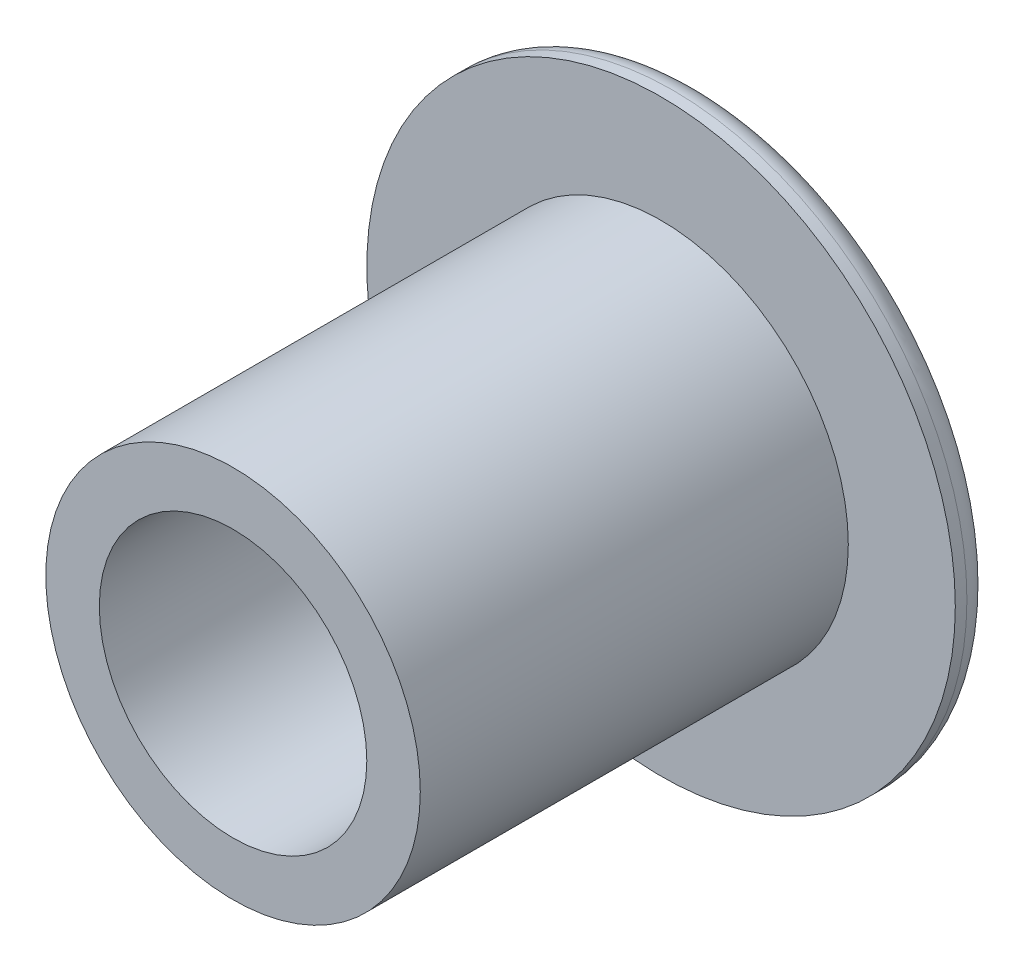
SolidWorks part; units mm, degrees
ref_plane "Front Plane" through (0, 0, 0) normal (0, 0, 1) x (1, 0, 0)
ref_plane "Top Plane" through (0, 0, 0) normal (0, 1, 0) x (1, 0, 0)
ref_plane "Right Plane" through (0, 0, 0) normal (1, 0, 0) x (0, 0, -1)
sketch "Sketch2" plane through (0, 0, 0) normal (0, 1, 0) x (1, 0, 0)
  line L0 (2.5, 0) -> (3.5, 0)
  line L1 (3.5, 0) -> (3.5, 8)
  line L2 (3.5, 8) -> (5.5, 8)
  line L3 (5.5, 8) -> (5.5, 8.5)
  line L4 (5.5, 8.5) -> (3, 10)
  line L5 (3, 10) -> (2.5, 10)
  line L6 (2.5, 10) -> (2.5, 0)
  line L7 (0, 0) -> (0, 10) construction
  dimension "D1" = 3.5
  dimension "D2" = 1
  dimension "D3" = 2
  dimension "D4" = 0.5
  dimension "D5" = 10
  dimension "D6" = 8
revolve "Revolve1" add sketch "Sketch2" angle 360 about L7
fillet "Fillet1" radius 0.5 2 edges at (3, 0, -10) (5.5, 0, -8.5)
sketch "Sketch4" plane through (0, 0, 0) normal (0, 1, 0) x (1, 0, 0)
  line L0 (0, 10.2815) -> (0, 7.7815) construction
  line L1 (0, 7.7815) -> (2.5, 7.7815)
  line L2 (2.5, 0) -> (2.5, 10) construction
  line L3 (0, 7.7815) -> (0, 10.2815)
  arc A0 (2.5, 7.7815) -> (0, 10.2815) centre (0, 7.7815) ccw
revolve "Revolve2" add sketch "Sketch4" angle 360 about L0
